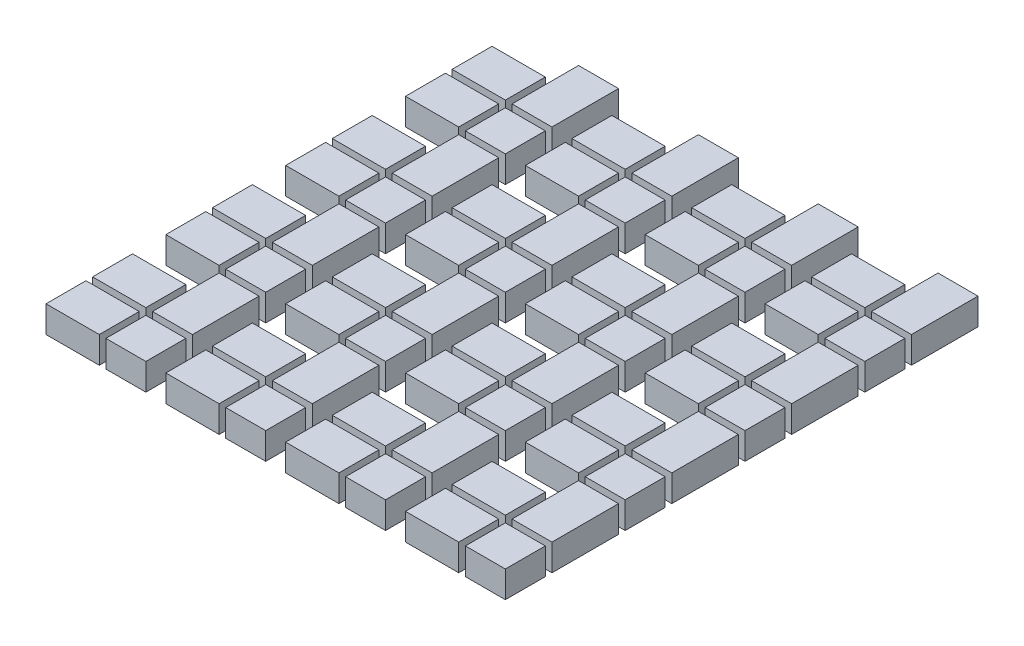
SolidWorks part; units mm, degrees
ref_plane "前视基准面" through (0, 0, 0) normal (0, 0, 1) x (1, 0, 0)
ref_plane "上视基准面" through (0, 0, 0) normal (0, 1, 0) x (1, 0, 0)
ref_plane "右视基准面" through (0, 0, 0) normal (1, 0, 0) x (0, 0, -1)
sketch "Sketch1" plane through (0, 0, 0) normal (0, 1, 0) x (1, 0, 0)
  line L0 (-5.08, 3.81) -> (-3.81, 3.81) construction
  line L1 (-3.81, 3.81) -> (3.81, 3.81)
  line L2 (-3.81, 3.81) -> (-3.81, -3.81)
  line L3 (-3.81, -3.81) -> (3.81, -3.81)
  line L4 (3.81, 3.81) -> (3.81, -3.81)
  line L5 (-3.81, 3.81) -> (3.81, -3.81) construction
  line L6 (-3.81, -3.81) -> (3.81, 3.81) construction
  line L7 (-5.08, 3.81) -> (-15.24, 3.81)
  line L8 (-5.08, 3.81) -> (-5.08, -3.81)
  line L9 (-5.08, -3.81) -> (-15.24, -3.81)
  line L10 (-15.24, 3.81) -> (-15.24, -3.81)
  line L11 (-5.08, 5.08) -> (-5.08, 3.81) construction
  line L12 (-5.08, 5.08) -> (-15.24, 5.08)
  line L13 (-5.08, 5.08) -> (-5.08, 12.7)
  line L14 (-5.08, 12.7) -> (-15.24, 12.7)
  line L15 (-15.24, 5.08) -> (-15.24, 12.7)
  line L16 (3.81, 5.08) -> (3.81, 3.81) construction
  line L17 (-3.81, 5.08) -> (3.81, 5.08)
  line L18 (-3.81, 5.08) -> (-3.81, 17.78)
  line L19 (-3.81, 17.78) -> (3.81, 17.78)
  line L20 (3.81, 5.08) -> (3.81, 17.78)
  line L21 (-5.08, 5.08) -> (-3.81, 5.08) construction
  point P0 (0, 0)
  dimension "D1" = 7.62
  dimension "D2" = 7.62
  dimension "D3" = 7.62
  dimension "D4" = 10.16
  dimension "D5" = 1.27
  dimension "D6" = 10.16
  dimension "D7" = 7.62
  dimension "D8" = 1.27
  dimension "D9" = 7.62
  dimension "D10" = 12.7
  dimension "D11" = 1.27
extrude "Boss-Extrude1" add sketch "Sketch1" along normal blind 5.08 contours L7 L10 L9 L8 | L17 L20 L19 L18 | L4 L1 L2 L3 | L14 L15 L12 L13
pattern_linear "LPattern1" count 4 spacing 22.86 along (-1, 0, 0) count 4 spacing 22.86 along (0, 0, 1) of "Boss-Extrude1"
